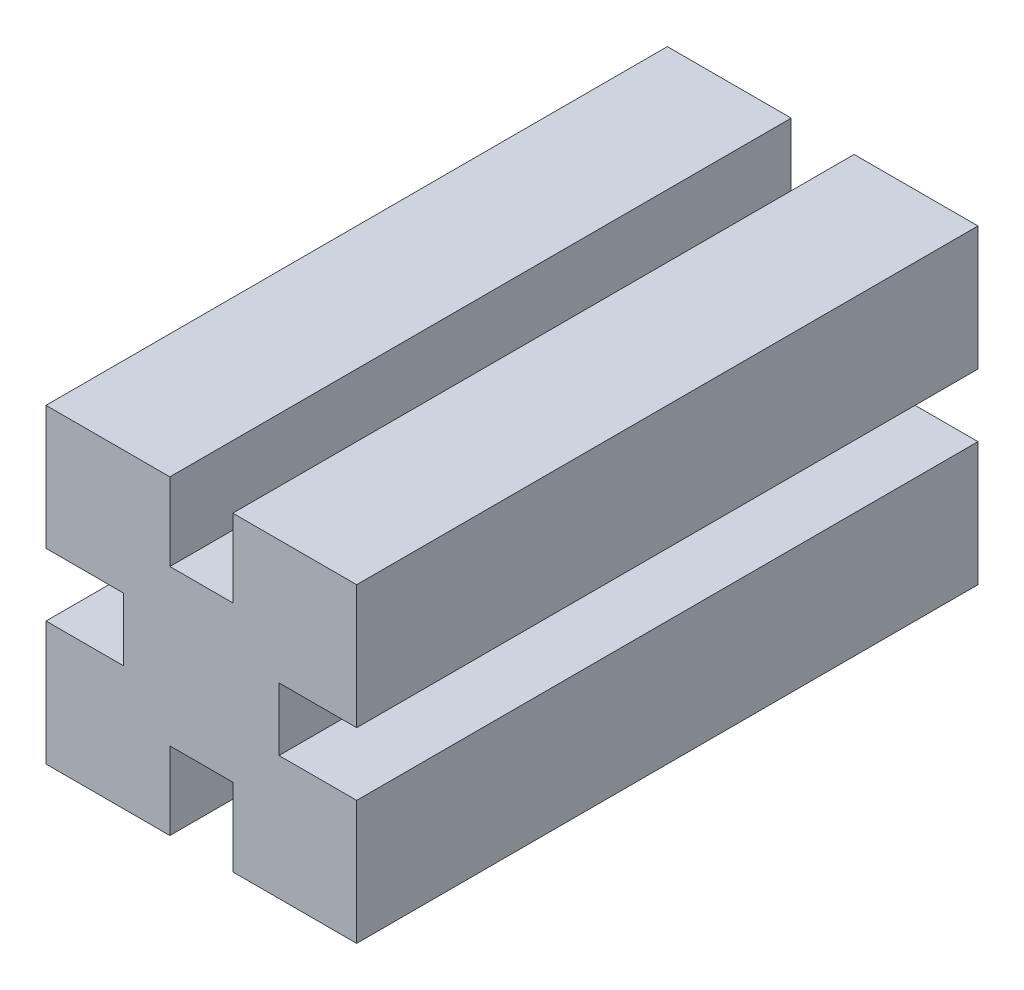
SolidWorks part; units mm, degrees
ref_plane "Front Plane" through (0, 0, 0) normal (0, 0, 1) x (1, 0, 0)
ref_plane "Top Plane" through (0, 0, 0) normal (0, 1, 0) x (1, 0, 0)
ref_plane "Right Plane" through (0, 0, 0) normal (1, 0, 0) x (0, 0, -1)
sketch "Sketch1" plane through (0, 0, 0) normal (0, 0, 1) x (1, 0, 0)
  line L1 (-20, 20) -> (20, 20)
  line L2 (-20, 20) -> (-20, -20)
  line L3 (-20, -20) -> (20, -20)
  line L4 (20, 20) -> (20, -20)
  line L5 (-20, 20) -> (20, -20) construction
  line L6 (-20, -20) -> (20, 20) construction
  line L7 (-30, 4.05) -> (-10, 4.05)
  line L8 (-30, 4.05) -> (-30, -4.05)
  line L9 (-30, -4.05) -> (-10, -4.05)
  line L10 (-10, 4.05) -> (-10, -4.05)
  line L11 (-30, 4.05) -> (-10, -4.05) construction
  line L12 (-30, -4.05) -> (-10, 4.05) construction
  line L13 (-4.05, 30) -> (4.05, 30)
  line L14 (-4.05, 30) -> (-4.05, 10)
  line L15 (-4.05, 10) -> (4.05, 10)
  line L16 (4.05, 30) -> (4.05, 10)
  line L17 (-4.05, 30) -> (4.05, 10) construction
  line L18 (-4.05, 10) -> (4.05, 30) construction
  line L19 (10, 4.05) -> (30, 4.05)
  line L20 (10, 4.05) -> (10, -4.05)
  line L21 (10, -4.05) -> (30, -4.05)
  line L22 (30, 4.05) -> (30, -4.05)
  line L23 (10, 4.05) -> (30, -4.05) construction
  line L24 (10, -4.05) -> (30, 4.05) construction
  line L25 (-4.05, -10) -> (4.05, -10)
  line L26 (-4.05, -10) -> (-4.05, -30)
  line L27 (-4.05, -30) -> (4.05, -30)
  line L28 (4.05, -10) -> (4.05, -30)
  line L29 (-4.05, -10) -> (4.05, -30) construction
  line L30 (-4.05, -30) -> (4.05, -10) construction
  line L31 (10, -10) -> (-10, -10) construction
  line L32 (10, -10) -> (10, 10) construction
  line L33 (10, 10) -> (-10, 10) construction
  line L34 (-10, -10) -> (-10, 10) construction
  line L35 (10, -10) -> (-10, 10) construction
  line L36 (10, 10) -> (-10, -10) construction
  point P0 (0, 0)
  point P6 (-20, 0)
  point P11 (0, 20)
  point P16 (20, 0)
  point P21 (0, -20)
  point P26 (0, 0)
  point P31 (-4.05, 14.1593)
  point P32 (-4.05, 11.3274)
  point P33 (-14.4497, 4.05)
  point P34 (-4.05, -11.3274)
  point P35 (14.4497, 4.05)
  dimension "D1" = 40
  dimension "D2" = 8.1
  dimension "D3" = 10
extrude "Boss-Extrude1" add sketch "Sketch1" along normal blind 80 contours L25 L28 L3 L4 L21 L20 L19 L1 L16 L15 L14 L2 L7 L10 L9 L26
